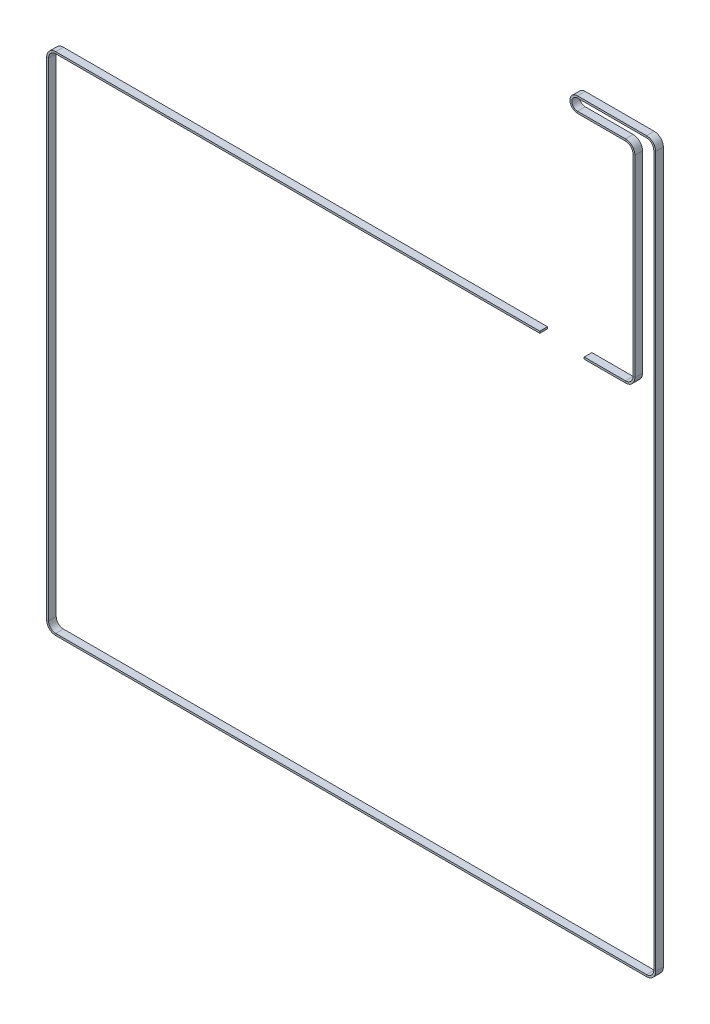
SolidWorks part; units mm, degrees
ref_plane "Front" through (0, 0, 0) normal (0, 0, 1) x (1, 0, 0)
ref_plane "Top" through (0, 0, 0) normal (0, 1, 0) x (1, 0, 0)
ref_plane "Right" through (0, 0, 0) normal (1, 0, 0) x (0, 0, -1)
sketch "Sketch1" plane through (0, 0, 2.2) normal (0, 0, 1) x (1, 0, 0)
  line L0 (377.3122, -142.2854) -> (431.3122, -142.2854)
  line L1 (377.3122, -152.6854) -> (414.8122, -152.6854)
  line L2 (421.4122, -159.2854) -> (421.4122, -309.932)
  line L3 (437.6872, -148.6604) -> (437.6872, -703.9854)
  line L4 (-37.0628, -703.9854) -> (-37.0628, -322.757)
  line L5 (431.3122, -710.3604) -> (-30.6878, -710.3604)
  line L6 (-30.6878, -316.382) -> (347.818, -316.382)
  line L8 (382.518, -316.432) -> (382.518, -319.932) construction
  line L9 (414.8122, -316.532) -> (382.518, -316.532)
  line L11 (347.818, -316.432) -> (347.818, -319.932) construction
  circle A0 centre (414.8122, -159.2854) radius 6.6 construction
  circle A1 centre (431.3122, -148.6604) radius 6.375 construction
  circle A2 centre (377.3122, -147.4854) radius 5.2 construction
  arc A3 (431.3122, -142.2854) -> (437.6872, -148.6604) centre (431.3122, -148.6604) cw
  arc A4 (377.3122, -152.6854) -> (377.3122, -142.2854) centre (377.3122, -147.4854) cw
  arc A5 (414.8122, -152.6854) -> (421.4122, -159.2854) centre (414.8122, -159.2854) cw
  circle A6 centre (-30.6878, -703.9854) radius 6.375 construction
  arc A7 (-30.6878, -710.3604) -> (-37.0628, -703.9854) centre (-30.6878, -703.9854) cw
  circle A8 centre (431.3122, -148.6604) radius 9 construction
  circle A9 centre (414.8122, -159.2854) radius 9 construction
  circle A10 centre (-30.6878, -322.757) radius 6.375 construction
  circle A11 centre (431.3122, -703.9854) radius 6.375 construction
  arc A12 (437.6872, -703.9854) -> (431.3122, -710.3604) centre (431.3122, -703.9854) cw
  arc A13 (-37.0628, -322.757) -> (-30.6878, -316.382) centre (-30.6878, -322.757) cw
  circle A14 centre (414.8122, -309.932) radius 6.6 construction
  arc A15 (421.4122, -309.932) -> (414.8122, -316.532) centre (414.8122, -309.932) cw
  circle A16 centre (414.8122, -309.932) radius 5.9875 construction
  circle A17 centre (-30.6878, -322.757) radius 5.9875 construction
  dimension "D1" = 12.75
ref_plane "Plane1" through (347.818, -316.382, 2.2) normal (1, 0, 0) x (0, 0, -1)
sketch "Sketch4" plane through (347.818, -316.382, 2.2) normal (1, 0, 0) x (0, 0, -1)
  line L0 (0, 167.7216) -> (0, -387.6034) construction
  line L1 (3, -0.75) -> (-3, -0.75)
  line L2 (3, -0.75) -> (3, 0.75)
  line L3 (3, 0.75) -> (-3, 0.75)
  line L4 (-3, -0.75) -> (-3, 0.75)
  line L5 (3, -0.75) -> (-3, 0.75) construction
  line L6 (3, 0.75) -> (-3, -0.75) construction
  line L7 (0, 0) -> (0, -12.75) construction
  point P0 (0, 0)
  dimension "D1" = 1.5
  dimension "D2" = 6
sweep "Sweep1" add profiles "Sketch4" path "Sketch1"
